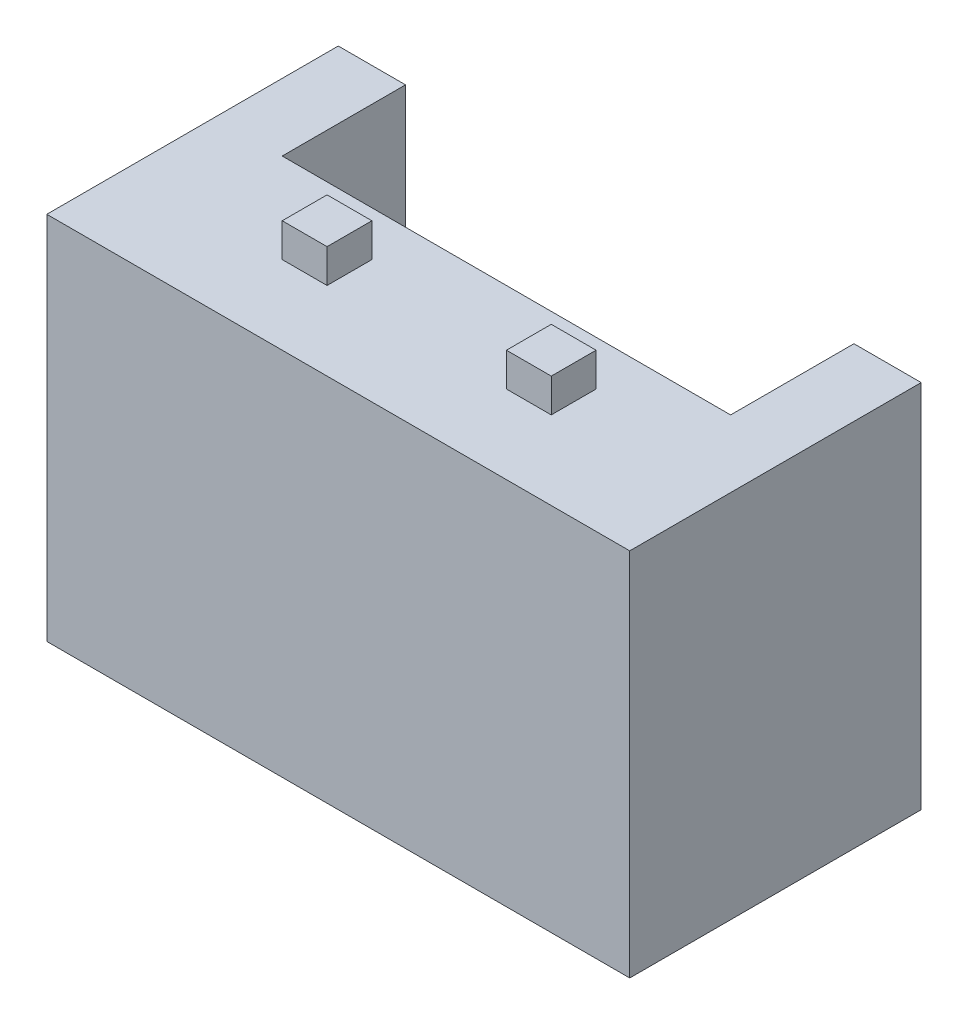
SolidWorks part; units mm, degrees
material "A-Стеклянное волокно"
ref_plane "Спереди" through (0, 0, 0) normal (0, 0, 1) x (1, 0, 0)
ref_plane "Сверху" through (0, 0, 0) normal (0, 1, 0) x (1, 0, 0)
ref_plane "Справа" through (0, 0, 0) normal (1, 0, 0) x (0, 0, -1)
sketch "Эскиз1" plane through (0, 0, 0) normal (0, 1, 0) x (1, 0, 0)
  line L0 (-10, 1) -> (10, 1)
  line L1 (-13, 6.5) -> (-10, 6.5)
  line L2 (13, 6.5) -> (13, -6.5)
  line L3 (13, -6.5) -> (-13, -6.5)
  line L4 (-13, 6.5) -> (-13, -6.5)
  line L5 (13, 6.5) -> (-13, -6.5) construction
  line L6 (13, -6.5) -> (-13, 6.5) construction
  line L7 (-10, 1) -> (-10, 6.5)
  line L8 (10, 1) -> (10, 6.5)
  line L9 (10, 6.5) -> (13, 6.5)
  point P0 (0, 0)
extrude "Бобышка-Вытянуть1" add sketch "Эскиз1" along normal blind 16.5
sketch "Эскиз2" plane through (0, 0, 0) normal (0, -1, 0) x (-1, 0, 0)
  line L0 (-3, -4) -> (-7, -4)
  line L1 (7, -4) -> (3, -4)
  line L2 (7, -4) -> (7, 1)
  line L3 (7, 1) -> (3, 1)
  line L4 (3, -4) -> (3, 1)
  line L5 (7, -4) -> (3, 1) construction
  line L6 (7, 1) -> (3, -4) construction
  line L7 (-3, -4) -> (-3, 1)
  line L8 (-3, 1) -> (-7, 1)
  line L9 (-7, -4) -> (-7, 1)
  line L10 (-3, -4) -> (-7, 1) construction
  line L11 (-3, 1) -> (-7, -4) construction
  point P0 (5, -1.5)
  point P5 (-5, -1.5)
extrude "Вырез-Вытянуть1" cut sketch "Эскиз2" against normal blind 2
sketch "Эскиз3" plane through (0, 16.5, 0) normal (0, 1, 0) x (1, 0, 0)
  line L1 (-6, -1) -> (-4, -1)
  line L2 (-6, -1) -> (-6, -3)
  line L3 (-6, -3) -> (-4, -3)
  line L4 (-4, -1) -> (-4, -3)
  line L5 (-6, -1) -> (-4, -3) construction
  line L6 (-6, -3) -> (-4, -1) construction
  line L7 (4, -1) -> (6, -1)
  line L8 (4, -1) -> (4, -3)
  line L9 (4, -3) -> (6, -3)
  line L10 (6, -1) -> (6, -3)
  line L11 (4, -1) -> (6, -3) construction
  line L12 (4, -3) -> (6, -1) construction
  point P0 (-5, -2)
  point P9 (5, -2)
extrude "Бобышка-Вытянуть2" add sketch "Эскиз3" along normal blind 1.5
